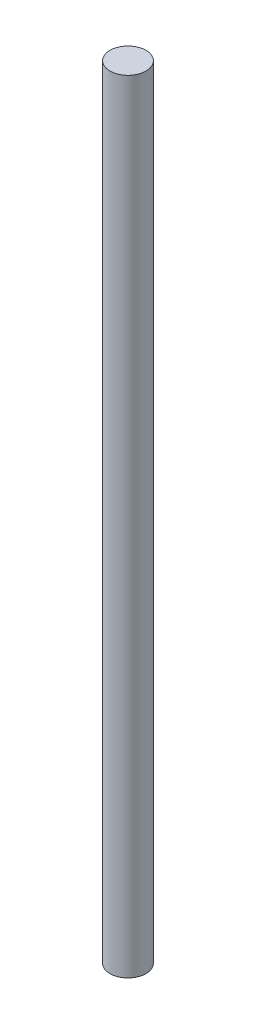
SolidWorks part; units mm, degrees
ref_plane "Front Plane" through (0, 0, 0) normal (0, 0, 1) x (1, 0, 0)
ref_plane "Top Plane" through (0, 0, 0) normal (0, 1, 0) x (1, 0, 0)
ref_plane "Right Plane" through (0, 0, 0) normal (1, 0, 0) x (0, 0, -1)
sketch "Sketch1" plane through (0, 0, 0) normal (0, 1, 0) x (1, 0, 0)
  circle A0 centre (0, 0) radius 1.59
  dimension "D1" = 3.18
extrude "Boss-Extrude1" add sketch "Sketch1" along normal blind 69.15
